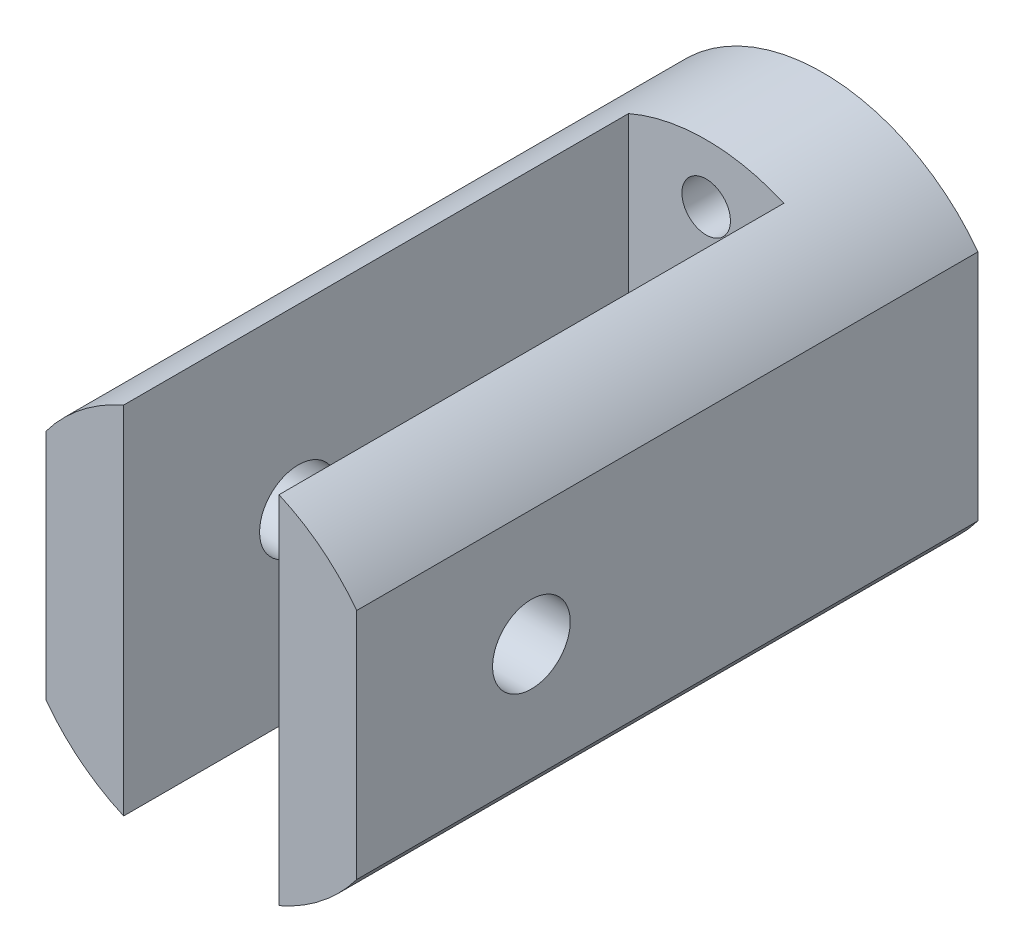
SolidWorks part; units mm, degrees
ref_plane "前视基准面" through (0, 0, 0) normal (0, 0, 1) x (1, 0, 0)
ref_plane "上视基准面" through (0, 0, 0) normal (0, 1, 0) x (1, 0, 0)
ref_plane "右视基准面" through (0, 0, 0) normal (1, 0, 0) x (0, 0, -1)
sketch "草图1" plane through (0, 0, 0) normal (0, 0, 1) x (1, 0, 0)
  circle A0 centre (0, 0) radius 10
extrude "凸台-拉伸2" add sketch "草图1" along normal blind 32 contours A0
sketch "草图3" plane through (0, 0, 0) normal (0, 1, 0) x (1, 0, 0)
  line L0 (0, 0) -> (0, -32) construction
  line L1 (-10, -32) -> (10, -32) construction
  line L2 (-4, -6) -> (4, -6)
  line L3 (4, -6) -> (4, -32)
  line L4 (4, -32) -> (-4, -32)
  line L5 (-4, -6) -> (-4, -32)
  line L6 (10, 0) -> (-10, 0) construction
  point P10 (0, -6)
  dimension "D1" = 8
  dimension "D2" = 6
extrude "切除-拉伸1" cut sketch "草图3" against normal through all both and the other way through all
sketch "草图4" plane through (0, 0, 0) normal (0, 1, 0) x (1, 0, 0)
  line L0 (0, 0) -> (0, -40) construction
  line L1 (-10, -32) -> (-4, -32) construction
  line L2 (-10, 0) -> (-8, 0)
  line L3 (-10, 0) -> (-10, -32)
  line L4 (-10, -32) -> (-8, -32)
  line L5 (-8, 0) -> (-8, -32)
  line L6 (10, -32) -> (8, -32)
  line L7 (10, 0) -> (10, -32)
  line L8 (10, 0) -> (8, 0)
  line L9 (8, 0) -> (8, -32)
  dimension "D1" = 2
extrude "切除-拉伸2" cut sketch "草图4" against normal through all both and the other way through all
sketch "草图5" plane through (0, 0, 0) normal (0, 0, -1) x (-1, 0, 0)
  line L0 (0, 10) -> (0, -10) construction
  line L1 (-8, 0) -> (8, 0) construction
  line L2 (-8, 6) -> (-8, -6) construction
  line L3 (8, -6) -> (8, 6) construction
  arc A0 (8, 6) -> (-8, 6) centre (0, 0) ccw construction
  arc A1 (-8, -6) -> (8, -6) centre (0, 0) ccw construction
  circle A2 centre (0, 7) radius 1.25
  circle A3 centre (0, -7) radius 1.25
  dimension "D1" = 14
extrude "切除-拉伸3" cut sketch "草图5" against normal through all
sketch "草图6" plane through (0, 0, 0) normal (1, 0, 0) x (0, 0, -1)
  line L0 (-32, 0) -> (0, 0) construction
  line L1 (-32, -6) -> (-32, 6) construction
  line L2 (0, 6) -> (0, -6) construction
  circle A0 centre (-23, 0) radius 2
  dimension "D1" = 23
extrude "切除-拉伸4" cut sketch "草图6" against normal through all both and the other way through all
